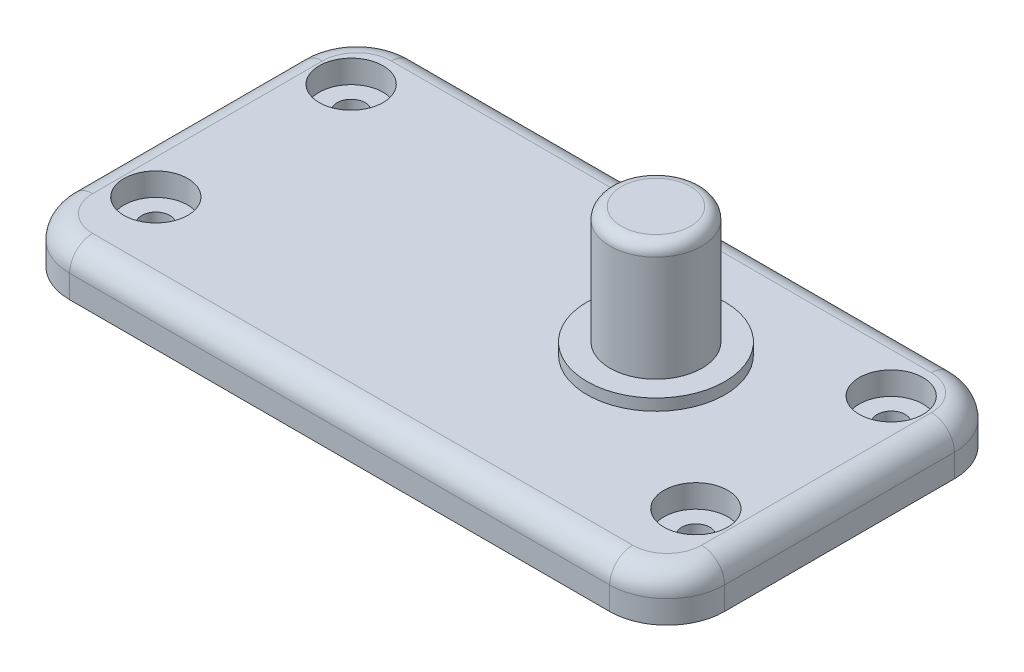
SolidWorks part; units mm, degrees
material "ABS"
ref_plane "Front" through (0, 0, 0) normal (0, 0, 1) x (1, 0, 0)
ref_plane "Top" through (0, 0, 0) normal (0, 1, 0) x (1, 0, 0)
ref_plane "Right" through (0, 0, 0) normal (1, 0, 0) x (0, 0, -1)
sketch "Sketch1" plane through (0, 0, 0) normal (0, 1, 0) x (1, 0, 0)
  line L1 (-28.5, -15) -> (28.5, -15)
  line L2 (-28.5, -15) -> (-28.5, 15)
  line L3 (-28.5, 15) -> (28.5, 15)
  line L4 (28.5, -15) -> (28.5, 15)
  point P4 (0, -15)
  point P6 (-28.5, 0)
  dimension "D1" = 57
  dimension "D2" = 30
extrude "Boss-Extrude1" add sketch "Sketch1" along normal blind 4
sketch "Sketch3" plane through (0, 4, 0) normal (0, 1, 0) x (1, 0, 0)
  line L0 (28.5, -15) -> (28.5, 15) construction
  line L1 (28.5, -15) -> (28.5, 15) construction
  circle A0 centre (10.18, 2.35) radius 4
  point P7 (28.5, 0)
  dimension "D1" = 8
  dimension "D2" = 18.32
  dimension "D3" = 2.35
extrude "Boss-Extrude2" add sketch "Sketch3" along normal blind 11.2
sketch "Sketch4" plane through (0, 4, 0) normal (0, 1, 0) x (1, 0, 0)
  circle A0 centre (10.18, 2.35) radius 6
  dimension "D1" = 12
extrude "Boss-Extrude3" add sketch "Sketch4" along normal blind 1
hole_wizard "CBORE for #2 Binding Head Machine Screw1" positions "Sketch5" profile "Sketch6" counterbore size "#2" standard "ANSI Inch" end condition through all
sketch "Sketch5" plane through (0, 4, 0) normal (0, 1, 0) x (1, 0, 0)
  line L0 (-23.5, -7.5) -> (23.5, -7.5) construction
  line L1 (23.5, -7.5) -> (23.5, 9.5) construction
  line L2 (23.5, 9.5) -> (-23.5, 9.5) construction
  line L3 (-23.5, 9.5) -> (-23.5, -7.5) construction
  line L5 (-28.5, 15) -> (-28.5, -15) construction
  line L6 (28.5, 15) -> (-28.5, 15) construction
  line L7 (28.5, 15) -> (-28.5, 15) construction
  point P0 (-23.5, 9.5)
  point P2 (-23.5, -7.5)
  point P4 (23.5, -7.5)
  point P6 (23.5, 9.5)
  point P24 (0, 9.5)
  point P27 (0, 15)
  dimension "D1" = 5
  dimension "D2" = 17
  dimension "D3" = 5.5
sketch "Sketch6" plane through (-23.5, 4, -9.5) normal (1, 0, 0) x (0, 0, 1)
  line L0 (0, 0) -> (0, 4)
  line L1 (0, 4) -> (1.2192, 4)
  line L3 (1.2192, 4) -> (1.2192, 2)
  line L4 (1.2192, 2) -> (2.7788, 2)
  line L5 (2.7788, 2) -> (2.7788, 0)
  line L7 (2.7788, 0) -> (0, 0)
  line L11 (0, -6.35) -> (0, 107.95) construction
  dimension "Thru Hole Dia." = 2.4384
  dimension "Thru Hole Depth" = 4
  dimension "C'Bore Dia." = 5.5575
  dimension "C'Bore Depth" = 2
fillet "Fillet1" radius 5 4 edges at (-28.5, 2, 15) (-28.5, 2, -15) (28.5, 2, -15) (28.5, 2, 15)
fillet "Fillet2" radius 2 8 edges at (-27.0355, 4, 13.5355) (-28.5, 4, 0) (-27.0355, 4, -13.5355) (0, 4, -15) (27.0355, 4, -13.5355) (28.5, 4, 0) (27.0355, 4, 13.5355) (0, 4, 15)
fillet "Fillet3" radius 1 1 edges at (10.18, 15.2, 1.65)
